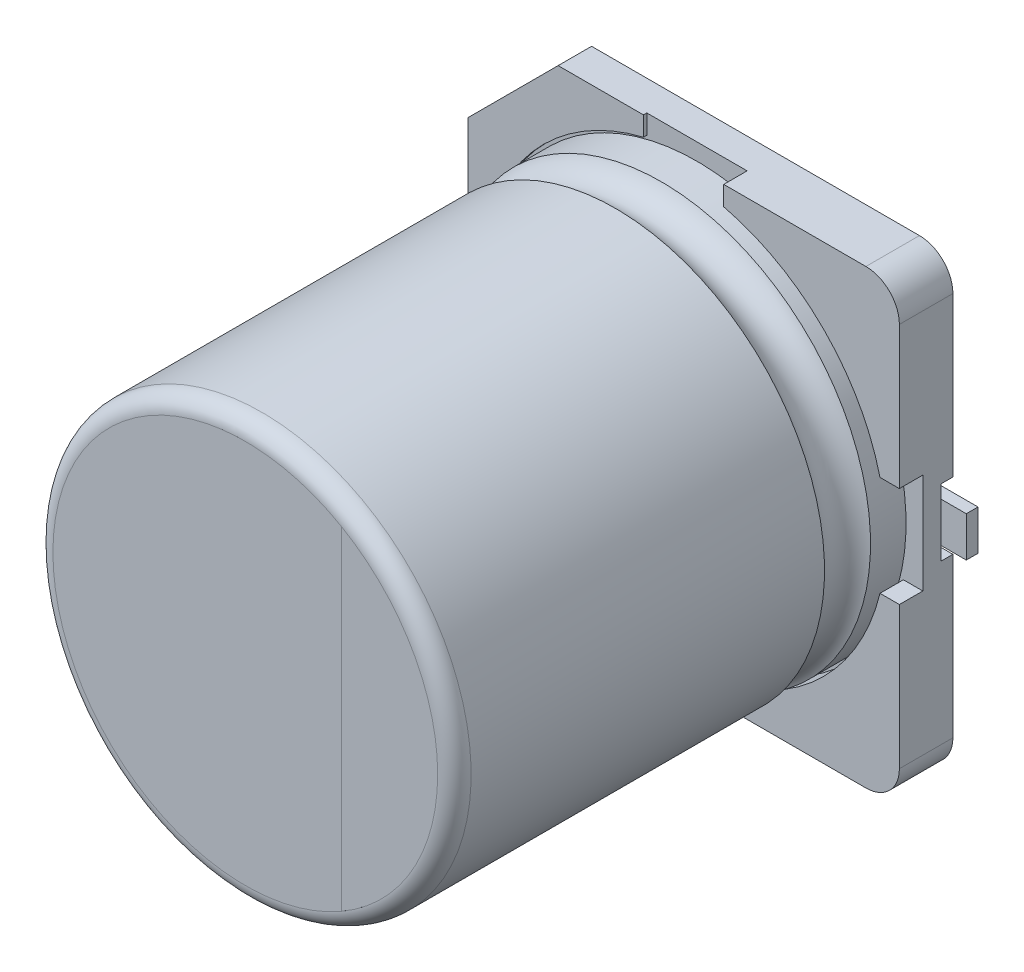
SolidWorks part; units mm, degrees
ref_plane "Front Plane" through (0, 0, 0) normal (0, 0, 1) x (1, 0, 0)
ref_plane "Top Plane" through (0, 0, 0) normal (0, 1, 0) x (1, 0, 0)
ref_plane "Right Plane" through (0, 0, 0) normal (1, 0, 0) x (0, 0, -1)
sketch "Sketch1" plane through (0, 0, 0) normal (0, 0, 1) x (1, 0, 0)
  line L0 (-6.75, 4.05) -> (-4.05, 6.75)
  line L1 (-4.05, -6.75) -> (5.75, -6.75)
  line L2 (-6.75, -4.05) -> (-6.75, 4.05)
  line L3 (-4.05, 6.75) -> (5.75, 6.75)
  line L4 (6.75, -5.75) -> (6.75, 5.75)
  line L5 (-6.75, -6.75) -> (6.75, 6.75) construction
  line L6 (-6.75, 6.75) -> (6.75, -6.75) construction
  line L7 (-4.05, -6.75) -> (-6.75, -4.05)
  arc A0 (6.75, -5.75) -> (5.75, -6.75) centre (5.75, -5.75) cw
  arc A1 (6.75, 5.75) -> (5.75, 6.75) centre (5.75, 5.75) ccw
  point P0 (0, 0)
  dimension "D3" = 1
  dimension "D1" = 13.5
  dimension "D2" = 13.5
extrude "Boss-Extrude1" add sketch "Sketch1" along normal blind 1.6
sketch "Sketch2" plane through (0, 0, 1.6) normal (0, 0, 1) x (1, 0, 0)
  line L0 (5.75, 6.75) -> (-4.05, 6.75) construction
  line L1 (-1.5, -6.75) -> (1.5, -6.75)
  line L2 (-1.5, -6.75) -> (-1.5, -6.1703)
  line L3 (-1.5, 6.75) -> (1.5, 6.75)
  line L4 (1.5, -6.75) -> (1.5, -6.1703)
  line L5 (-1.5, -6.75) -> (-1.3775, -6.1988) construction
  line L6 (-1.5, 6.75) -> (-1.3775, 6.1988) construction
  line L7 (6.75, -5.75) -> (6.75, 5.75) construction
  line L8 (-6.75, -1.5) -> (-6.1703, -1.5)
  line L9 (-6.75, -1.5) -> (-6.75, 1.5)
  line L10 (-6.75, 1.5) -> (-6.1703, 1.5)
  line L11 (6.75, -1.5) -> (6.75, 1.5)
  line L12 (-6.75, -1.5) -> (-6.1988, -1.3775) construction
  line L13 (-6.75, 1.5) -> (-6.1988, 1.3775) construction
  line L14 (1.5, 1.5) -> (1.5, 6.1703) construction
  line L15 (1.5, 6.1703) -> (1.5, 6.75)
  line L16 (0.3333, 1.5) -> (1.3775, 6.1988) construction
  line L17 (1.3775, 6.1988) -> (1.5, 6.75) construction
  line L18 (-1.3775, 6.1988) -> (-0.3333, 1.5) construction
  line L19 (0, 0) -> (0.3333, -1.5) construction
  line L20 (-1.5, 1.5) -> (-1.5, 6.1703) construction
  line L21 (-1.5, 6.1703) -> (-1.5, 6.75)
  line L22 (-6.1703, 1.5) -> (-1.5, 1.5) construction
  line L23 (-0.3333, 1.5) -> (0.3333, 1.5) construction
  line L24 (-6.1988, 1.3775) -> (-1.5, 0.3333) construction
  line L25 (0, 0) -> (1.5, -0.3333) construction
  line L26 (-6.1988, -1.3775) -> (-1.5, -0.3333) construction
  line L27 (0, 0) -> (1.5, 0.3333) construction
  line L28 (-6.1703, -1.5) -> (-1.5, -1.5) construction
  line L29 (-0.3333, -1.5) -> (0.3333, -1.5) construction
  line L30 (-1.5, -6.1703) -> (-1.5, -1.5) construction
  line L31 (-1.5, -0.3333) -> (-1.5, 0.3333) construction
  line L32 (-1.3775, -6.1988) -> (-0.3333, -1.5) construction
  line L33 (-0.3333, -1.5) -> (0, 0) construction
  line L34 (0.3333, -1.5) -> (1.3775, -6.1988) construction
  line L35 (1.3775, -6.1988) -> (1.5, -6.75) construction
  line L36 (1.5, -6.1703) -> (1.5, -1.5) construction
  line L37 (1.5, -0.3333) -> (1.5, 0.3333) construction
  line L38 (1.5, -1.5) -> (6.1703, -1.5) construction
  line L39 (6.1703, -1.5) -> (6.75, -1.5)
  line L40 (1.5, -0.3333) -> (6.1988, -1.3775) construction
  line L41 (6.1988, -1.3775) -> (6.75, -1.5) construction
  line L42 (1.5, 0.3333) -> (6.1988, 1.3775) construction
  line L43 (6.1988, 1.3775) -> (6.75, 1.5) construction
  line L44 (1.5, 1.5) -> (6.1703, 1.5) construction
  line L45 (6.1703, 1.5) -> (6.75, 1.5)
  line L46 (-1.5, 1.5) -> (-0.3333, 1.5) construction
  line L47 (-1.5, 0.3333) -> (-1.5, 1.5) construction
  line L48 (-1.5, -1.5) -> (-1.5, -0.3333) construction
  line L49 (-1.5, -1.5) -> (-0.3333, -1.5) construction
  line L50 (0.3333, -1.5) -> (1.5, -1.5) construction
  line L51 (1.5, -1.5) -> (1.5, -0.3333) construction
  line L52 (1.5, 0.3333) -> (1.5, 1.5) construction
  line L53 (0.3333, 1.5) -> (1.5, 1.5) construction
  line L54 (-0.3333, 1.5) -> (0, 0) construction
  line L55 (0, 0) -> (0.3333, 1.5) construction
  line L56 (-1.5, 0.3333) -> (0, 0) construction
  line L57 (-1.5, -0.3333) -> (0, 0) construction
  arc A0 (-1.5, 6.1703) -> (-6.1703, 1.5) centre (0, 0) ccw
  arc A1 (1.3775, 6.1988) -> (-1.3775, 6.1988) centre (0, 0) ccw construction
  arc A2 (6.1988, -1.3775) -> (6.1988, 1.3775) centre (0, 0) ccw construction
  arc A3 (6.1703, 1.5) -> (1.5, 6.1703) centre (0, 0) ccw
  arc A4 (-1.3775, -6.1988) -> (1.3775, -6.1988) centre (0, 0) ccw construction
  arc A5 (1.5, -6.1703) -> (6.1703, -1.5) centre (0, 0) ccw
  arc A6 (-6.1988, 1.3775) -> (-6.1988, -1.3775) centre (0, 0) ccw construction
  arc A7 (-6.1703, -1.5) -> (-1.5, -6.1703) centre (0, 0) ccw
  arc A8 (-6.1703, 1.5) -> (-6.1988, 1.3775) centre (0, 0) ccw construction
  arc A9 (-6.1988, -1.3775) -> (-6.1703, -1.5) centre (0, 0) ccw construction
  arc A10 (-1.5, -6.1703) -> (-1.3775, -6.1988) centre (0, 0) ccw construction
  arc A11 (1.3775, -6.1988) -> (1.5, -6.1703) centre (0, 0) ccw construction
  arc A12 (6.1703, -1.5) -> (6.1988, -1.3775) centre (0, 0) ccw construction
  arc A13 (6.1988, 1.3775) -> (6.1703, 1.5) centre (0, 0) ccw construction
  arc A14 (-1.3775, 6.1988) -> (-1.5, 6.1703) centre (0, 0) ccw construction
  arc A15 (1.5, 6.1703) -> (1.3775, 6.1988) centre (0, 0) ccw construction
  dimension "D1" = 12.7
  dimension "D2" = 3
  dimension "D3" = 3
extrude "Cut-Extrude1" cut sketch "Sketch2" against normal blind 0.7
sketch "Sketch3" plane through (0, 0, 1.6) normal (0, 0, 1) x (1, 0, 0)
  line L0 (-4.05, -6.75) -> (-1.5, -6.75) construction
  line L1 (-1.5, -6.75) -> (-1.5, -6.1703) construction
  line L2 (-6.1703, -1.5) -> (-6.75, -1.5) construction
  line L3 (-6.75, -1.5) -> (-6.75, -4.05) construction
  line L4 (-6.75, -4.05) -> (-4.05, -6.75) construction
  line L5 (-6.75, 4.05) -> (-6.75, 1.5) construction
  line L6 (-6.75, 1.5) -> (-6.1703, 1.5) construction
  line L7 (-1.5, 6.1703) -> (-1.5, 6.75) construction
  line L8 (-1.5, 6.75) -> (-4.05, 6.75) construction
  line L9 (-4.05, 6.75) -> (-6.75, 4.05) construction
  line L10 (-4.05, -6.75) -> (-1.5, -6.75)
  line L11 (-1.5, -6.75) -> (-1.5, -6.1703)
  line L12 (-6.1703, -1.5) -> (-6.75, -1.5)
  line L13 (-6.75, -1.5) -> (-6.75, -4.05)
  line L14 (-6.75, -4.05) -> (-4.05, -6.75)
  line L15 (-6.75, 4.05) -> (-6.75, 1.5)
  line L16 (-6.75, 1.5) -> (-6.1703, 1.5)
  line L17 (-1.5, 6.1703) -> (-1.5, 6.75)
  line L18 (-1.5, 6.75) -> (-4.05, 6.75)
  line L19 (-4.05, 6.75) -> (-6.75, 4.05)
  arc A0 (-6.1703, -1.5) -> (-1.5, -6.1703) centre (0, 0) ccw construction
  arc A1 (-1.5, 6.1703) -> (-6.1703, 1.5) centre (0, 0) ccw construction
  arc A2 (-6.1703, -1.5) -> (-1.5, -6.1703) centre (0, 0) ccw
  arc A3 (-1.5, 6.1703) -> (-6.1703, 1.5) centre (0, 0) ccw
extrude "Cut-Extrude2" cut sketch "Sketch3" against normal blind 0.6
sketch "Sketch7" plane through (0, 0, 0) normal (0, 0, -1) x (-1, 0, 0)
  line L5 (0, 0) -> (-3.75, 0) construction
  line L6 (-6.75, -5.75) -> (-6.75, 5.75) construction
  line L7 (-2.75, 1) -> (-3.55, 0.6) construction
  line L8 (-2.75, -1) -> (-6.75, -1)
  line L10 (-2.75, -1) -> (-2.75, 0) construction
  line L11 (-2.75, 1) -> (-6.75, 1)
  line L12 (-6.75, -1) -> (-6.75, 1)
  line L13 (-3.55, -0.6) -> (-6.75, 1) construction
  line L14 (-3.55, 0.6) -> (-6.75, -1) construction
  line L15 (-2.75, 0) -> (-2.75, 1) construction
  line L16 (-3.75, 0) -> (-4.75, 0) construction
  line L18 (-4.75, 0) -> (-6.75, 0) construction
  line L19 (-2.75, -1) -> (-3.55, -0.6) construction
  line L20 (0, 0) -> (0, 50000) construction
  line L21 (2.75, -1) -> (6.75, -1)
  line L22 (6.75, -1) -> (6.75, 1)
  line L23 (2.75, 1) -> (6.75, 1)
  arc A2 (-2.75, -1) -> (-2.75, 1) centre (-2.75, 0) ccw
  arc A3 (-2.75, 1) -> (-3.55, 0.6) centre (-2.75, 0) ccw construction
  arc A4 (-3.55, 0.6) -> (-3.75, 0) centre (-2.75, 0) ccw construction
  arc A5 (-3.75, 0) -> (-3.55, -0.6) centre (-2.75, 0) ccw construction
  arc A6 (-3.55, -0.6) -> (-2.75, -1) centre (-2.75, 0) ccw construction
  arc A7 (2.75, -1) -> (2.75, 1) centre (2.75, 0) cw
  point P4 (-4.75, 0)
  dimension "D1" = 4
  dimension "D2" = 2
extrude "Cut-Extrude4" cut sketch "Sketch7" against normal blind 0.35
sketch "Sketch5" plane through (0, 0, 0) normal (1, 0, 0) x (0, 0, -1)
  line L0 (-0.9, -6.25) -> (-1.9626, -6.25)
  line L1 (-1.9626, -6.25) -> (-3.3374, -6.25) construction
  line L2 (-3.3374, -6.25) -> (-14.4, -6.25)
  line L3 (0, 0) -> (-50000, 0) construction
  line L5 (-0.9, 1.5) -> (-0.9, -49998.5) construction
  line L6 (-14.4, -6.25) -> (-14.4, 0)
  line L7 (-14.4, 0) -> (-0.9, 0)
  line L8 (-0.9, 0) -> (-0.9, -6.25)
  arc A0 (-3.3374, -6.25) -> (-1.9626, -6.25) centre (-2.65, -6.55) cw
  point P2 (0, 0)
  point P7 (-2.9, -6.25)
  point P12 (-3.2738, -6.25)
  point P17 (0, 0)
  dimension "D3" = 0.75
  dimension "D4" = 6.25
  dimension "D5" = 0.3
  dimension "D1" = 13.5
  dimension "D2" = 1.75
revolve "Revolve1" add sketch "Sketch5" angle 360 about L3
fillet "Fillet1" radius 0.5 1 edges at (-6.25, 0, 14.4)
sketch "Sketch6" plane through (0, 0, 14.4) normal (0, 0, 1) x (1, 0, 0)
  line L0 (2.875, 4.9796) -> (2.875, -4.9796)
  line L1 (0, 0) -> (5.75, 0) construction
  circle A0 centre (0, 0) radius 5.75 construction
  arc A1 (2.875, 4.9796) -> (2.875, -4.9796) centre (0, 0) cw
  point P8 (2.875, 0)
extrude "Cut-Extrude3" cut sketch "Sketch6" against normal blind 0.001
sketch "Sketch9" plane through (0, 0, 0.35) normal (0, 0, -1) x (-1, 0, 0)
  line L0 (0, 0) -> (0, 50000) construction
  line L1 (7.5, 0.6) -> (7.5, -0.6)
  line L2 (2.75, 0.6) -> (7.5, 0.6)
  line L3 (7.5, -0.6) -> (2.75, -0.6)
  line L5 (-7.5, 0.6) -> (-7.5, -0.6)
  line L7 (-6.75, -0.6) -> (-2.75, -0.6)
  line L8 (-2.75, 0.6) -> (-6.75, 0.6)
  line L9 (-7.5, -0.6) -> (-2.75, -0.6)
  line L10 (-2.75, 0.6) -> (-7.5, 0.6)
  arc A0 (2.75, -0.6) -> (2.75, 0.6) centre (2.75, 0) cw
  arc A3 (-2.75, -0.6) -> (-2.75, 0.6) centre (-2.75, 0) ccw
  arc A4 (-2.75, -0.6) -> (-2.75, 0.6) centre (-2.75, 0) ccw
  dimension "D2" = 7.5
  dimension "D1" = 0.4
extrude "Boss-Extrude2" add sketch "Sketch9" along normal up to surface (0.35 mm away) separate body up to face at (0.2384, 0, 0)
